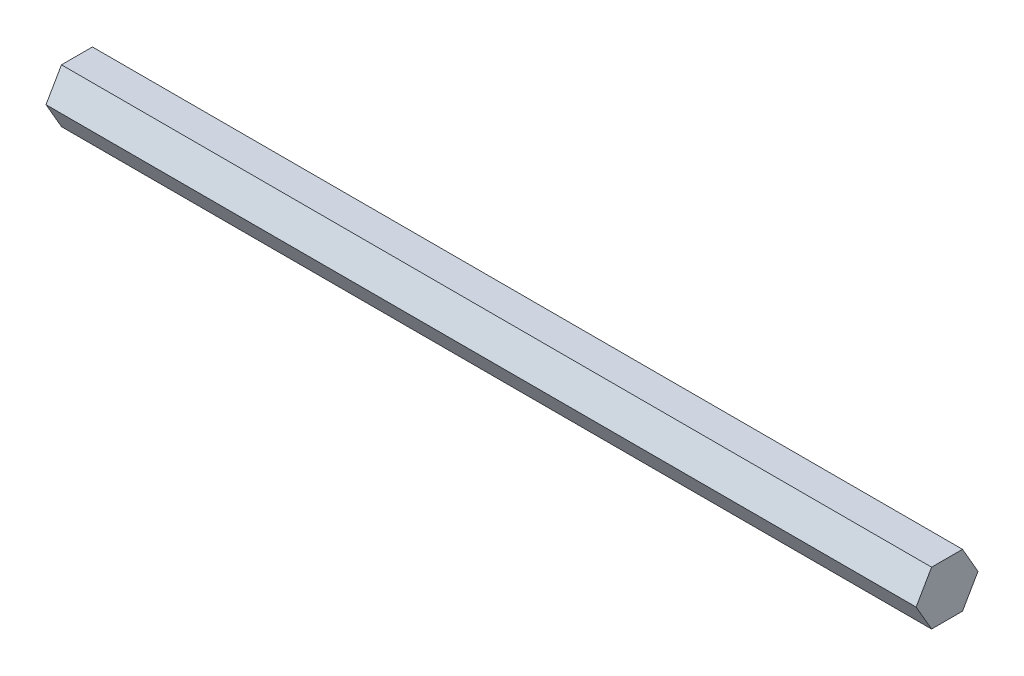
SolidWorks part; units mm, degrees
material "6061 Alloy"
ref_plane "Front" through (0, 0, 0) normal (0, 0, 1) x (1, 0, 0)
ref_plane "Top" through (0, 0, 0) normal (0, 1, 0) x (1, 0, 0)
ref_plane "Right" through (0, 0, 0) normal (1, 0, 0) x (0, 0, -1)
sketch "Sketch1" plane through (0, 0, 0) normal (1, 0, 0) x (0, 0, -1)
  line L1 (3.6662, 6.35) -> (-3.6662, 6.35)
  line L2 (-3.6662, 6.35) -> (-7.3323, 0)
  line L3 (-7.3323, 0) -> (-3.6662, -6.35)
  line L4 (-3.6662, -6.35) -> (3.6662, -6.35)
  line L5 (3.6662, -6.35) -> (7.3323, 0)
  line L6 (7.3323, 0) -> (3.6662, 6.35)
  circle A0 centre (0, 0) radius 6.35 construction
  dimension "D1" = 12.7
extrude "Boss-Extrude1" add sketch "Sketch1" along normal blind 206.1972
sketch "Sketch2" [suppressed] plane through (92.075, 0, 0) normal (1, 0, 0) x (0, 0, -1)
  circle A0 centre (0, 0) radius 2.413
  dimension "D1" = 4.826
extrude "Cut-Extrude1" [suppressed] cut sketch "Sketch2" against normal blind 25.4
sketch "Sketch3" [suppressed] plane through (0, 3.175, 5.4993) normal (0, 0.5, 0.866) x (1, 0, 0)
  line L0 (0, 3.6662) -> (0, -3.6662) construction
  line L1 (0, 0) -> (47.0154, 0) construction
  circle A0 centre (47.0154, 0) radius 1.778
  dimension "D2" = 3.556
  dimension "D1" = 47.0154
extrude "Cut-Extrude2" [suppressed] cut sketch "Sketch3" against normal blind 25.4
sketch "Sketch4" [suppressed] plane through (22.352, 0, 0) normal (1, 0, 0) x (0, 0, -1)
  circle A0 centre (0, 0) radius 2.54
  dimension "D1" = 5.08
extrude "Cut-Extrude3" [suppressed] cut sketch "Sketch4" against normal through all
